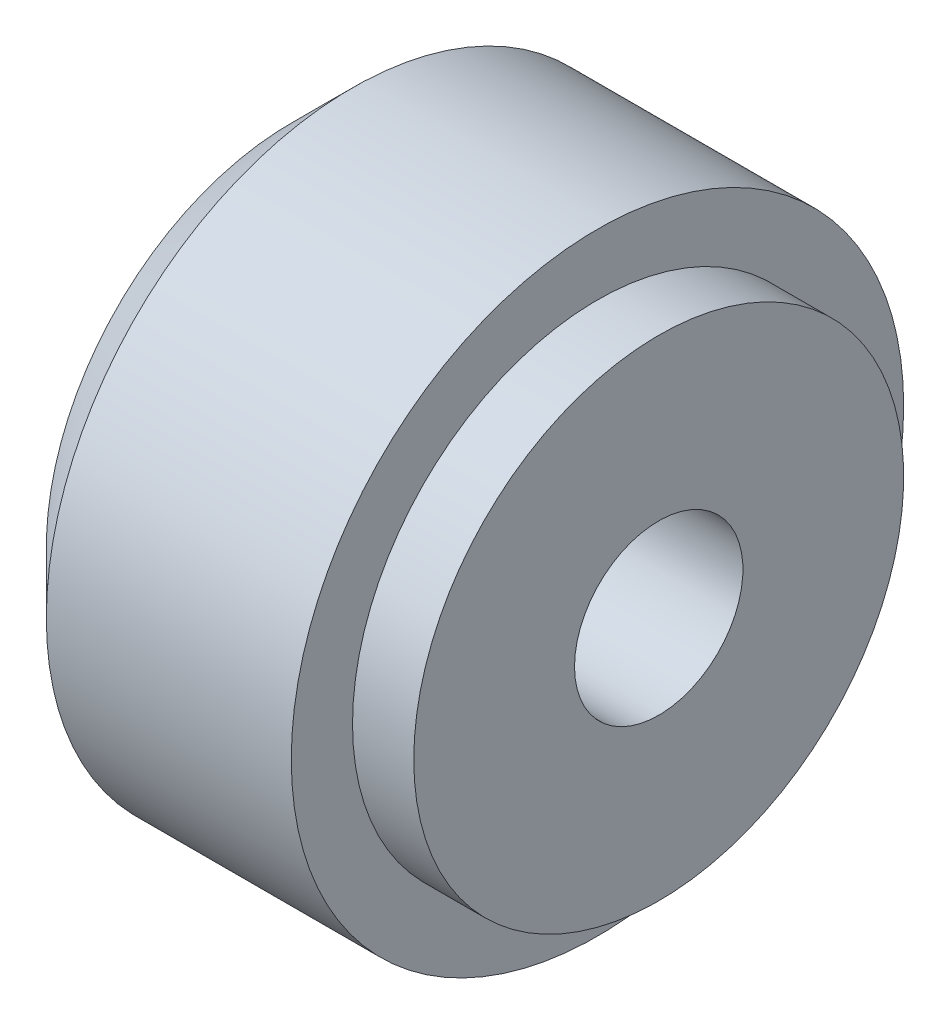
SolidWorks part; units mm, degrees
material "PET"
ref_plane "Front Plane" through (0, 0, 0) normal (0, 0, 1) x (1, 0, 0)
ref_plane "Top Plane" through (0, 0, 0) normal (0, 1, 0) x (1, 0, 0)
ref_plane "Right Plane" through (0, 0, 0) normal (1, 0, 0) x (0, 0, -1)
sketch "Sketch1" plane through (0, 0, 0) normal (0, 0, 1) x (1, 0, 0)
  line L0 (0, 0) -> (0, 8)
  line L1 (0, 8) -> (-2, 8)
  line L2 (-2, 8) -> (-2, 10)
  line L3 (-2, 10) -> (-12, 10)
  line L4 (-12, 10) -> (-12, 0)
  line L5 (-12, 0) -> (0, 0)
  line L6 (0, 0) -> (32.4289, 0) construction
  point P3 (-1, 8)
  dimension "D1" = 16
  dimension "D2" = 20
  dimension "D3" = 2
  dimension "D4" = 10
revolve "body" add sketch "Sketch1" angle 360 about L6
chamfer "front_chamfers" distance 2 angle 45 1 edges at (-12, 0, 10)
sketch "Sketch2" plane through (-12, 0, 0) normal (-1, 0, 0) x (0, 0, 1)
  point P0 (0, 0)
hole_wizard "mounting_screw" positions "Sketch2" profile "Sketch3" counterbore size "M5" standard "DIN"
sketch "Sketch3" plane through (-12, 0, 0) normal (0, 1, 0) x (0, 0, 1)
  line L0 (0, 0) -> (0, 13.6524)
  line L1 (0, 13.6524) -> (2.75, 12)
  line L2 (2.75, 12) -> (2.75, 5.4)
  line L3 (2.75, 5.4) -> (5, 5.4)
  line L4 (5, 5.4) -> (5, 0)
  line L5 (5, 0) -> (0, 0)
  line L10 (0, 13.6524) -> (-2.75, 12) construction
  line L11 (0, -6.35) -> (0, 107.95) construction
  dimension "Hole Dia." = 5.5
  dimension "Hole Depth" = 12
  dimension "C'Bore Dia." = 10
  dimension "C'Bore Depth" = 5.4
  dimension "Drill Angle" = 118
